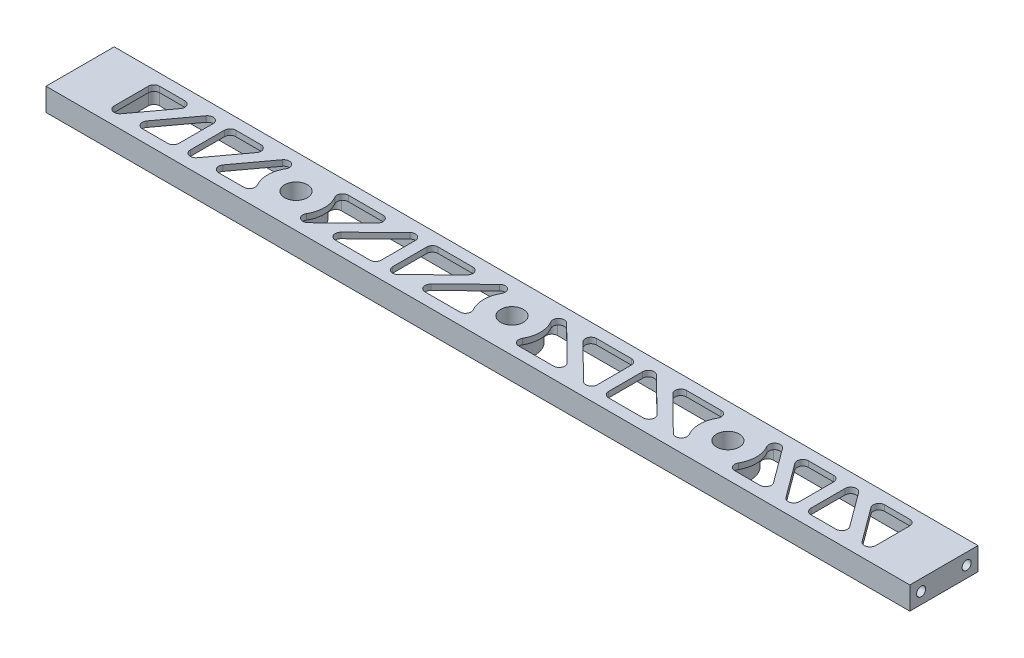
SolidWorks part; units mm, degrees
material "6061 Alloy"
ref_plane "Front Plane" through (0, 0, 0) normal (0, 0, 1) x (1, 0, 0)
ref_plane "Top Plane" through (0, 0, 0) normal (0, 1, 0) x (1, 0, 0)
ref_plane "Right Plane" through (0, 0, 0) normal (1, 0, 0) x (0, 0, -1)
sketch "Sketch1" plane through (0, 0, 0) normal (1, 0, 0) x (0, 0, -1)
  line L1 (-19.05, -6.35) -> (19.05, -6.35)
  line L2 (-19.05, -6.35) -> (-19.05, 6.35)
  line L3 (-19.05, 6.35) -> (19.05, 6.35)
  line L4 (19.05, -6.35) -> (19.05, 6.35)
  line L5 (-19.05, -6.35) -> (19.05, 6.35) construction
  line L6 (-19.05, 6.35) -> (19.05, -6.35) construction
  point P0 (0, 0)
  dimension "D1" = 38.1
  dimension "D2" = 12.7
extrude "Boss-Extrude1" add sketch "Sketch1" along normal mid plane 482.6
hole_wizard "1/4-20 Tapped Hole1" positions "3DSketch1" profile "Sketch3" tap size "1/4-20" standard "ANSI Inch"
sketch3d "3DSketch1"
  line L4 (241.3, 0, 19.05) -> (241.3, 0, 12.7) construction
  line L5 (241.3, 6.35, 19.05) -> (241.3, -6.35, 19.05) construction
  line L6 (241.3, 0, 12.7) -> (241.3, 0, -12.7) construction
  line L7 (241.3, 0, -12.7) -> (241.3, 0, -19.05) construction
  line L8 (241.3, -6.35, -19.05) -> (241.3, 6.35, -19.05) construction
  point P0 (241.3, 0, 12.7)
  point P2 (241.3, 0, -12.7)
  dimension "D1" = 25.4
sketch "Sketch3" plane through (241.3, 0, 12.7) normal (0, 1, 0) x (0, 0, -1)
  line L0 (0, 0) -> (0, 20.5838)
  line L1 (0, 20.5838) -> (2.5527, 19.05)
  line L2 (2.5527, 19.05) -> (2.5527, 0)
  line L5 (2.5527, 0) -> (0, 0)
  line L10 (0, 20.5838) -> (-2.5527, 19.05) construction
  line L11 (0, -6.35) -> (0, 107.95) construction
  dimension "Tap Drill Dia." = 5.1054
  dimension "Tap Drill Depth" = 19.05
  dimension "Drill Angle" = 118
sketch "Sketch2" plane through (0, 6.35, 0) normal (0, 1, 0) x (1, 0, 0)
  line L0 (0, 0) -> (241.3, 0) construction
  line L1 (241.3, -19.05) -> (241.3, 19.05) construction
  circle A0 centre (0, 0) radius 6.35
  circle A1 centre (120.65, 0) radius 6.35
  dimension "D1" = 12.7
extrude "Cut-Extrude1" cut sketch "Sketch2" against normal through all
sketch "Sketch4" plane through (0, -6.35, 0) normal (0, -1, 0) x (1, 0, 0)
  line L1 (9.525, 15.875) -> (111.125, 15.875)
  line L2 (130.175, 15.875) -> (212.725, 15.875)
  line L3 (215.9, 12.7) -> (215.9, -12.7)
  line L4 (212.725, -15.875) -> (130.175, -15.875)
  line L5 (111.125, -15.875) -> (9.525, -15.875)
  line L6 (241.3, 0) -> (215.9, 0) construction
  line L8 (241.3, 19.05) -> (241.3, -19.05) construction
  line L9 (241.3, 19.05) -> (-241.3, 19.05) construction
  arc A0 (7.62, -10.16) -> (7.62, 10.16) centre (0, 0) ccw
  arc A1 (113.03, 10.16) -> (113.03, -10.16) centre (120.65, 0) ccw
  arc A2 (128.27, 10.16) -> (128.27, -10.16) centre (120.65, 0) cw
  arc A3 (128.27, 10.16) -> (130.175, 15.875) centre (130.175, 12.7) cw
  arc A4 (128.27, -10.16) -> (130.175, -15.875) centre (130.175, -12.7) ccw
  arc A5 (113.03, -10.16) -> (111.125, -15.875) centre (111.125, -12.7) cw
  arc A6 (215.9, -12.7) -> (212.725, -15.875) centre (212.725, -12.7) cw
  arc A7 (212.725, 15.875) -> (215.9, 12.7) centre (212.725, 12.7) cw
  arc A8 (7.62, -10.16) -> (9.525, -15.875) centre (9.525, -12.7) ccw
  arc A9 (7.62, 10.16) -> (9.525, 15.875) centre (9.525, 12.7) cw
  arc A10 (113.03, 10.16) -> (111.125, 15.875) centre (111.125, 12.7) ccw
  dimension "D3" = 25.4
  dimension "D4" = 3.175
  dimension "D1" = 12.7
  dimension "D2" = 3.175
extrude "Cut-Extrude2" cut sketch "Sketch4" against normal blind 9.525
mirror "Mirror2" about plane through (0, 0, 0) normal (1, 0, 0) of "Cut-Extrude2", "Cut-Extrude1", "1/4-20 Tapped Hole1"
sketch "Sketch5" plane through (0, 3.175, 0) normal (0, -1, 0) x (1, 0, 0)
  line L0 (0, 19.05) -> (0, -19.05) construction
  line L1 (241.3, 19.05) -> (-241.3, 19.05) construction
  line L2 (241.3, -19.05) -> (-241.3, -19.05) construction
  line L3 (-212.725, 9.525) -> (-212.725, -9.525)
  line L4 (-209.55, -12.7) -> (-195.4852, -12.7)
  line L5 (-192.931, -7.6392) -> (-206.9957, 11.4108)
  line L6 (-193.7636, 12.7) -> (-179.6989, 12.7)
  line L7 (-176.5239, 9.525) -> (-176.5239, -9.525)
  line L8 (-182.2532, -11.4108) -> (-196.3179, 7.6392)
  line L11 (-212.725, 0) -> (-215.9, 0) construction
  line L12 (-215.9, -12.7) -> (-215.9, 12.7) construction
  line L13 (-186.7313, 12.7) -> (-186.7313, 15.875) construction
  line L14 (-202.5176, -12.7) -> (-202.5176, -15.875) construction
  line L15 (-130.175, -15.875) -> (-212.725, -15.875) construction
  line L16 (-212.725, 15.875) -> (-130.175, 15.875) construction
  line L17 (-199.9634, 1.8858) -> (-194.8548, 5.6575) construction
  line L18 (-170.1739, 9.525) -> (-170.1739, -9.525)
  line L19 (-166.9989, -12.7) -> (-152.9341, -12.7)
  line L21 (-150.3799, -7.6392) -> (-164.4446, 11.4108)
  line L22 (-176.5239, 0) -> (-170.1739, 0) construction
  line L23 (-136.525, 0) -> (-133.35, 0) construction
  line L25 (-151.2125, 12.7) -> (-137.1478, 12.7)
  line L26 (-153.7668, 7.6392) -> (-139.702, -11.4108)
  line L27 (-157.4122, 1.8858) -> (-152.3037, 5.6575) construction
  line L28 (-104.1522, -12.7) -> (-84.7855, -12.7)
  line L29 (-82.559, -7.2615) -> (-101.9257, 11.7885)
  line L30 (-86.0418, 12.7) -> (-66.675, 12.7)
  line L32 (-63.5, 9.525) -> (-63.5, -9.525)
  line L33 (-68.9015, -11.7885) -> (-88.2682, 7.2615)
  line L34 (-107.95, 0) -> (-104.775, 0) construction
  line L35 (-92.2424, 2.2635) -> (-87.7894, 6.7905) construction
  line L36 (-15.875, 0) -> (-12.7, 0) construction
  line L37 (-57.15, 9.525) -> (-57.15, -9.525)
  line L38 (-53.975, -12.7) -> (-34.6082, -12.7)
  line L39 (-32.3818, -7.2615) -> (-51.7485, 11.7885)
  line L40 (-38.091, 7.2615) -> (-18.7243, -11.7885)
  line L41 (-35.8645, 12.7) -> (-16.4978, 12.7)
  line L42 (-63.5, 0) -> (-57.15, 0) construction
  line L43 (-42.0651, 2.2635) -> (-37.6122, 6.7905) construction
  arc A0 (-193.7636, 12.7) -> (-196.3179, 7.6392) centre (-193.7636, 9.525) ccw
  arc A1 (-179.6989, 12.7) -> (-176.5239, 9.525) centre (-179.6989, 9.525) cw
  arc A2 (-176.5239, -9.525) -> (-182.2532, -11.4108) centre (-179.6989, -9.525) cw
  arc A3 (-195.4852, -12.7) -> (-192.931, -7.6392) centre (-195.4852, -9.525) ccw
  arc A4 (-212.725, -9.525) -> (-209.55, -12.7) centre (-209.55, -9.525) ccw
  arc A5 (-212.725, 9.525) -> (-206.9957, 11.4108) centre (-209.55, 9.525) cw
  arc A6 (-152.9341, -12.7) -> (-150.3799, -7.6392) centre (-152.9341, -9.525) ccw
  arc A7 (-170.1739, -9.525) -> (-166.9989, -12.7) centre (-166.9989, -9.525) ccw
  arc A11 (-170.1739, 9.525) -> (-164.4446, 11.4108) centre (-166.9989, 9.525) cw
  arc A12 (-134.3982, 7.9375) -> (-134.3982, -7.9375) centre (-120.65, 0) ccw
  arc A13 (-128.27, 10.16) -> (-128.27, -10.16) centre (-120.65, 0) ccw construction
  arc A14 (-151.2125, 12.7) -> (-153.7668, 7.6392) centre (-151.2125, 9.525) ccw
  arc A16 (-137.1478, 12.7) -> (-134.3982, 7.9375) centre (-137.1478, 9.525) cw
  arc A17 (-134.3982, -7.9375) -> (-139.702, -11.4108) centre (-137.1478, -9.525) cw
  arc A18 (-106.9018, -7.9375) -> (-106.9018, 7.9375) centre (-120.65, 0) ccw
  arc A19 (-84.7855, -12.7) -> (-82.559, -7.2615) centre (-84.7855, -9.525) ccw
  arc A20 (-63.5, -9.525) -> (-68.9015, -11.7885) centre (-66.675, -9.525) cw
  arc A22 (-66.675, 12.7) -> (-63.5, 9.525) centre (-66.675, 9.525) cw
  arc A23 (-86.0418, 12.7) -> (-88.2682, 7.2615) centre (-86.0418, 9.525) ccw
  arc A25 (-113.03, -10.16) -> (-113.03, 10.16) centre (-120.65, 0) ccw construction
  arc A27 (-106.9018, 7.9375) -> (-101.9257, 11.7885) centre (-104.1522, 9.525) cw
  arc A28 (-106.9018, -7.9375) -> (-104.1522, -12.7) centre (-104.1522, -9.525) ccw
  arc A29 (-13.7482, 7.9375) -> (-13.7482, -7.9375) centre (0, 0) ccw
  arc A31 (-7.62, 10.16) -> (-7.62, -10.16) centre (0, 0) ccw construction
  arc A32 (-13.7482, -7.9375) -> (-18.7243, -11.7885) centre (-16.4978, -9.525) cw
  arc A34 (-13.7482, 7.9375) -> (-16.4978, 12.7) centre (-16.4978, 9.525) ccw
  arc A35 (-38.091, 7.2615) -> (-35.8645, 12.7) centre (-35.8645, 9.525) cw
  arc A36 (-34.6082, -12.7) -> (-32.3818, -7.2615) centre (-34.6082, -9.525) ccw
  arc A37 (-57.15, -9.525) -> (-53.975, -12.7) centre (-53.975, -9.525) ccw
  arc A38 (-57.15, 9.525) -> (-51.7485, 11.7885) centre (-53.975, 9.525) cw
  dimension "D1" = 3.175
  dimension "D2" = 3.175
  dimension "D3" = 6.35
extrude "Cut-Extrude3" cut sketch "Sketch5" against normal through all
mirror "Mirror3" about plane through (0, 0, 0) normal (1, 0, 0) of "Cut-Extrude3"
